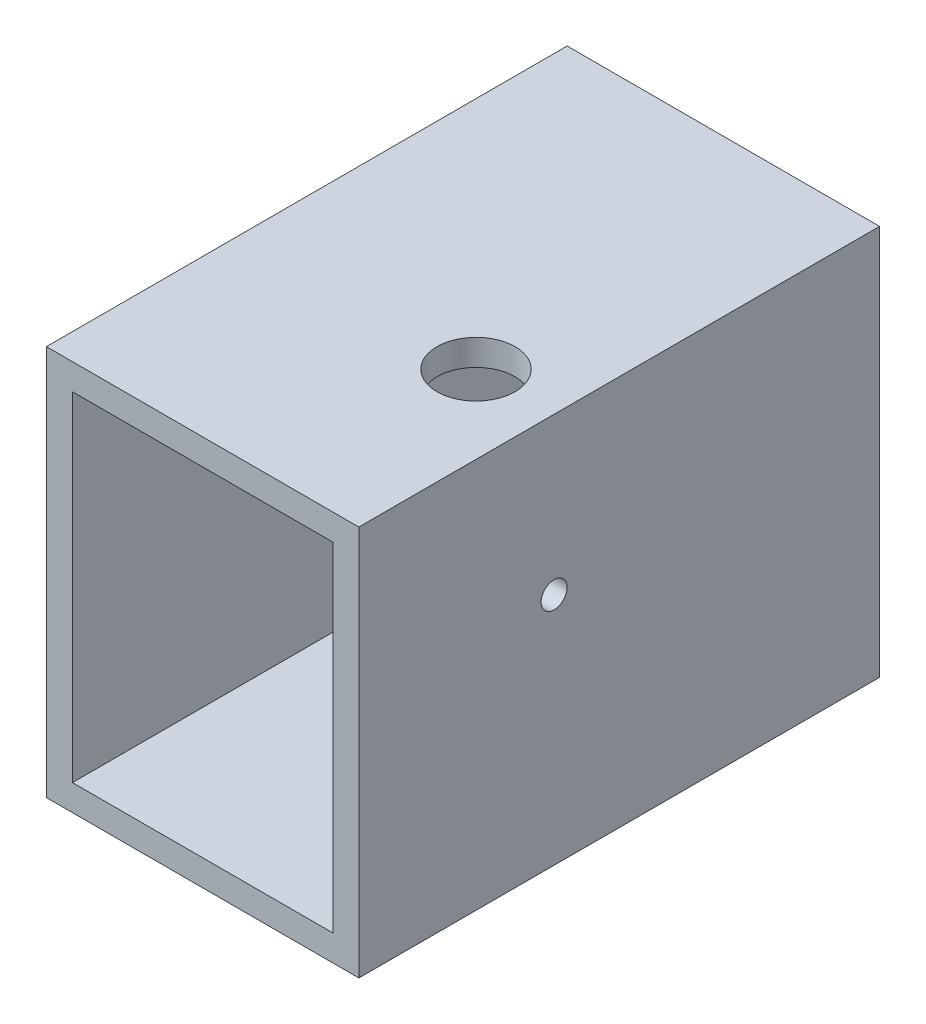
SolidWorks part; units mm, degrees
ref_plane "Front Plane" through (0, 0, 0) normal (0, 0, 1) x (1, 0, 0)
ref_plane "Top Plane" through (0, 0, 0) normal (0, 1, 0) x (1, 0, 0)
ref_plane "Right Plane" through (0, 0, 0) normal (1, 0, 0) x (0, 0, -1)
sketch "Sketch1" plane through (0, 0, 0) normal (0, 0, 1) x (1, 0, 0)
  line L1 (0, 0) -> (120, 0)
  line L2 (0, 0) -> (0, -150)
  line L3 (0, -150) -> (120, -150)
  line L4 (120, 0) -> (120, -150)
  dimension "D1" = 150
  dimension "D2" = 120
extrude "Boss-Extrude1" add sketch "Sketch1" along normal blind 200
sketch "Sketch2" plane through (0, 0, 200) normal (0, 0, 1) x (1, 0, 0)
  line L0 (10, -10) -> (10, -140)
  line L5 (10, -140) -> (110, -140)
  line L6 (110, -10) -> (110, -140)
  line L7 (10, -10) -> (110, -10)
extrude "Cut-Extrude1" cut sketch "Sketch2" against normal blind 195
sketch "Sketch3" plane through (120, 0, 0) normal (1, 0, 0) x (0, 0, -1)
  line L0 (-200, -150) -> (-200, 0) construction
  line L1 (-200, 0) -> (0, 0) construction
  circle A0 centre (-125, -60) radius 5
  dimension "D1" = 75
  dimension "D2" = 60
extrude "Cut-Extrude2" cut sketch "Sketch3" against normal blind 120
sketch "Sketch4" plane through (0, -150, 0) normal (0, -1, 0) x (1, 0, 0)
  line L0 (0, 200) -> (120, 200) construction
  line L1 (120, 200) -> (120, 0) construction
  circle A0 centre (90, 125) radius 15
  dimension "D1" = 75
  dimension "D2" = 30
extrude "Cut-Extrude3" cut sketch "Sketch4" against normal blind 24 from offset 130
